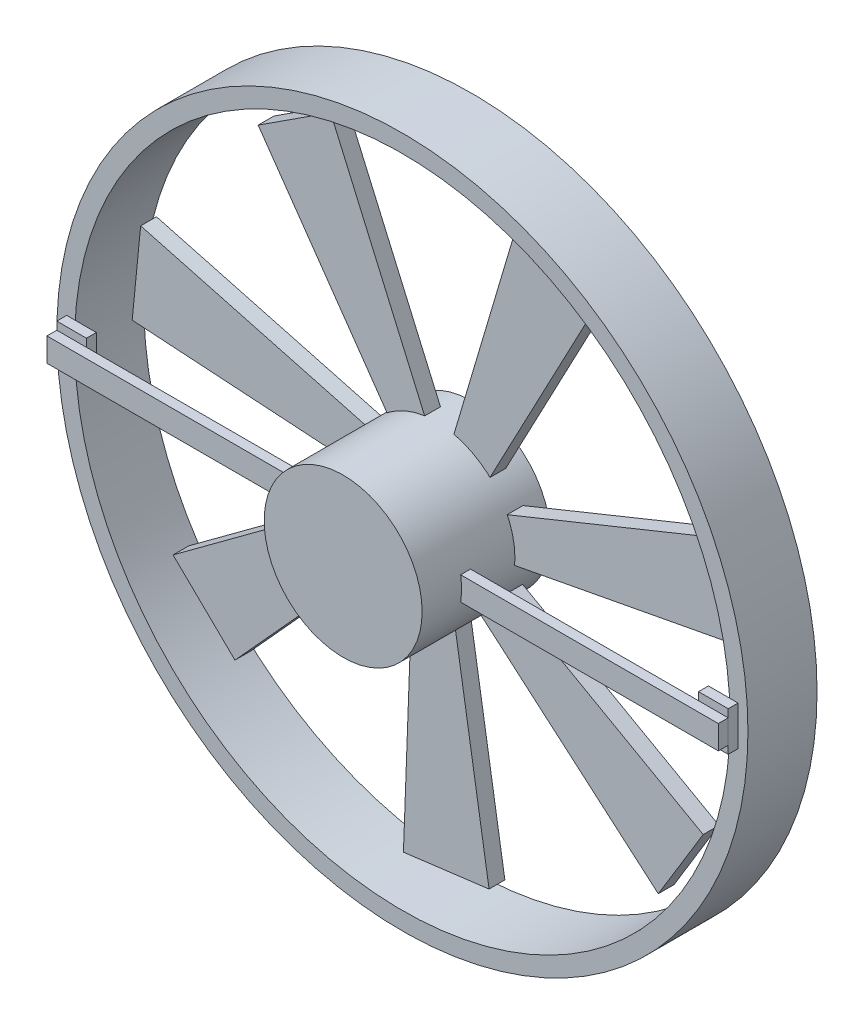
SolidWorks part; units mm, degrees
ref_plane "Front Plane" through (0, 0, 0) normal (0, 0, 1) x (1, 0, 0)
ref_plane "Top Plane" through (0, 0, 0) normal (0, 1, 0) x (1, 0, 0)
ref_plane "Right Plane" through (0, 0, 0) normal (1, 0, 0) x (0, 0, -1)
sketch "Sketch1" plane through (0, 0, 0) normal (0, 0, 1) x (1, 0, 0)
  circle A0 centre (0, 250) radius 175
  circle A1 centre (0, 250) radius 166
extrude "Fan_housing_OD350_ASSUMED" add sketch "Sketch1" along normal blind 35 from offset 380 separate body
sketch "Sketch2" plane through (0, 0, 0) normal (0, 0, 1) x (1, 0, 0)
  circle A0 centre (0, 250) radius 40
extrude "Fan_motor_envelope_ASSUMED" add sketch "Sketch2" along normal blind 65 from offset 380 separate body
sketch "Sketch3" plane through (0, 0, 0) normal (0, 0, 1) x (1, 0, 0)
  line L0 (31.6407, 245.218) -> (156.8638, 268.9145)
  line L1 (156.8638, 268.9145) -> (141.8434, 309.9704)
  line L2 (141.8434, 309.9704) -> (32.4161, 265.6588)
  line L3 (32.4161, 265.6588) -> (31.6407, 245.218)
extrude "Blade_1_VISUAL_ONLY" add sketch "Sketch3" along normal blind 8 from offset 390 separate body
sketch "Sketch4" plane through (0, 0, 0) normal (0, 0, 1) x (1, 0, 0)
  line L0 (23.4664, 271.7561) -> (83.015, 384.434)
  line L1 (83.015, 384.434) -> (41.5511, 398.2886)
  line L2 (41.5511, 398.2886) -> (7.9686, 285.107)
  line L3 (7.9686, 285.107) -> (23.4664, 271.7561)
extrude "Blade_2_VISUAL_ONLY" add sketch "Sketch4" along normal blind 8 from offset 390 separate body
sketch "Sketch5" plane through (0, 0, 0) normal (0, 0, 1) x (1, 0, 0)
  line L0 (-2.3786, 281.9115) -> (-53.3458, 398.722)
  line L1 (-53.3458, 398.722) -> (-90.03, 374.9424)
  line L2 (-90.03, 374.9424) -> (-22.4794, 278.119)
  line L3 (-22.4794, 278.119) -> (-2.3786, 281.9115)
extrude "Blade_3_VISUAL_ONLY" add sketch "Sketch5" along normal blind 8 from offset 390 separate body
sketch "Sketch6" plane through (0, 0, 0) normal (0, 0, 1) x (1, 0, 0)
  line L0 (-26.4324, 268.0368) -> (-149.5361, 301.0192)
  line L1 (-149.5361, 301.0192) -> (-153.8167, 257.5121)
  line L2 (-153.8167, 257.5121) -> (-36, 249.9568)
  line L3 (-36, 249.9568) -> (-26.4324, 268.0368)
extrude "Blade_4_VISUAL_ONLY" add sketch "Sketch6" along normal blind 8 from offset 390 separate body
sketch "Sketch7" plane through (0, 0, 0) normal (0, 0, 1) x (1, 0, 0)
  line L0 (-30.5821, 240.5801) -> (-133.1227, 164.898)
  line L1 (-133.1227, 164.898) -> (-101.7763, 134.425)
  line L2 (-101.7763, 134.425) -> (-22.4118, 221.8271)
  line L3 (-22.4118, 221.8271) -> (-30.5821, 240.5801)
extrude "Blade_5_VISUAL_ONLY" add sketch "Sketch7" along normal blind 8 from offset 390 separate body
sketch "Sketch8" plane through (0, 0, 0) normal (0, 0, 1) x (1, 0, 0)
  line L0 (-11.7028, 220.2167) -> (-16.4652, 92.8603)
  line L1 (-16.4652, 92.8603) -> (26.9037, 98.3682)
  line L2 (26.9037, 98.3682) -> (8.0529, 214.9122)
  line L3 (8.0529, 214.9122) -> (-11.7028, 220.2167)
extrude "Blade_6_VISUAL_ONLY" add sketch "Sketch8" along normal blind 8 from offset 390 separate body
sketch "Sketch9" plane through (0, 0, 0) normal (0, 0, 1) x (1, 0, 0)
  line L0 (15.9889, 222.2808) -> (112.5909, 139.152)
  line L1 (112.5909, 139.152) -> (135.3247, 176.4933)
  line L2 (135.3247, 176.4933) -> (32.4536, 234.4192)
  line L3 (32.4536, 234.4192) -> (15.9889, 222.2808)
extrude "Blade_7_VISUAL_ONLY" add sketch "Sketch9" along normal blind 8 from offset 390 separate body
sketch "Sketch10" plane through (0, 0, 0) normal (0, 0, 1) x (1, 0, 0)
  line L1 (-170, 240) -> (-155, 240)
  line L2 (-170, 240) -> (-170, 260)
  line L3 (-170, 260) -> (-155, 260)
  line L4 (-155, 240) -> (-155, 260)
extrude "Motor_support_strut" add sketch "Sketch10" along normal blind 5 from offset 415 separate body
sketch "Sketch11" plane through (0, 0, 0) normal (0, 0, 1) x (1, 0, 0)
  line L1 (155, 240) -> (170, 240)
  line L2 (155, 240) -> (155, 260)
  line L3 (155, 260) -> (170, 260)
  line L4 (170, 240) -> (170, 260)
extrude "Boss-Extrude11" add sketch "Sketch11" along normal blind 5 from offset 415 separate body
sketch "Sketch12" plane through (0, 0, 0) normal (0, 0, 1) x (1, 0, 0)
  line L1 (-170, 244) -> (170, 244)
  line L2 (-170, 244) -> (-170, 256)
  line L3 (-170, 256) -> (170, 256)
  line L4 (170, 244) -> (170, 256)
extrude "Motor_support_bridge" add sketch "Sketch12" along normal blind 5 from offset 420 separate body
